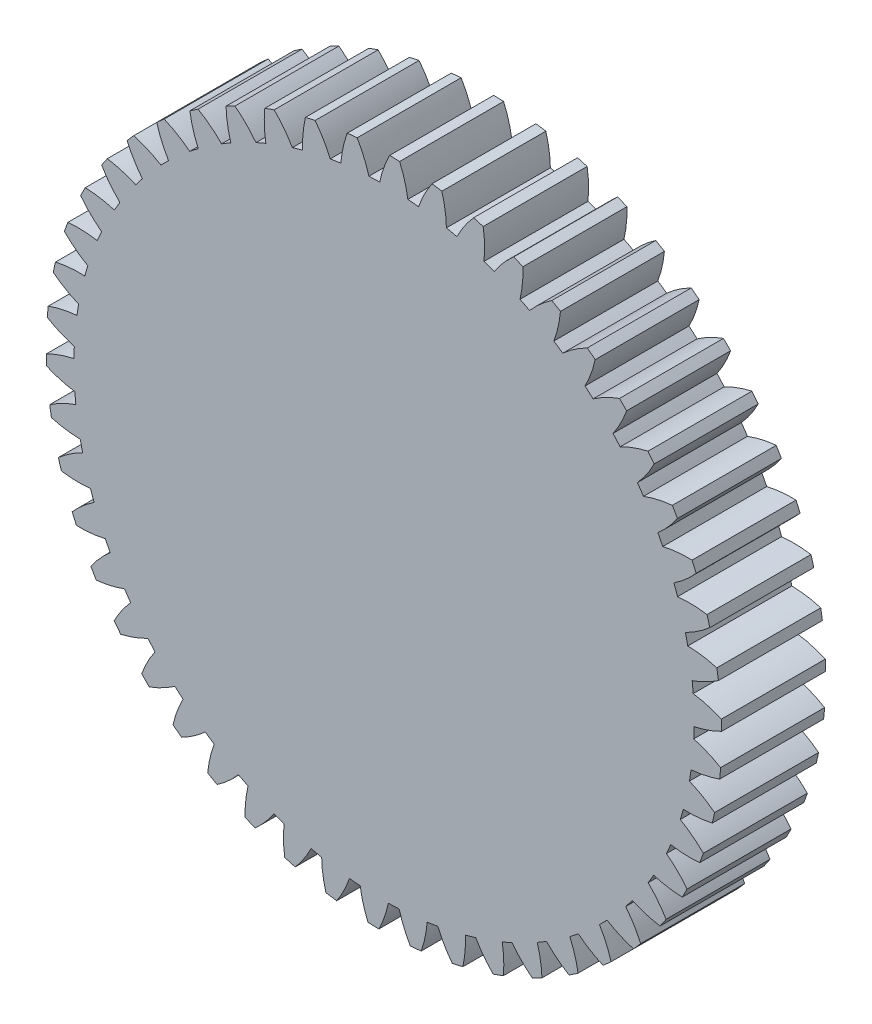
SolidWorks part; units mm, degrees
ref_plane "Front Plane" through (0, 0, 0) normal (0, 0, 1) x (1, 0, 0)
ref_plane "Top Plane" through (0, 0, 0) normal (0, 1, 0) x (1, 0, 0)
ref_plane "Right Plane" through (0, 0, 0) normal (1, 0, 0) x (0, 0, -1)
sketch "Sketch1" plane through (0, 0, 0) normal (0, 0, 1) x (1, 0, 0)
  circle A0 centre (0, 0) radius 104
  dimension "D1" = 208
extrude "Boss-Extrude1" add sketch "Sketch1" along normal blind 32.0177
sketch "Sketch2" plane through (0, 0, 32.0177) normal (0, 0, 1) x (1, 0, 0)
  line L0 (0, 104) -> (0, 0) construction
  line L1 (0, 0) -> (32.1394, 88.3022) construction
  line L2 (32.1394, 88.3022) -> (0, 100) construction
  line L3 (-3.1412, 99.9507) -> (0, 0) construction
  circle A1 centre (0, 0) radius 104
  arc A2 (1.745, 103.9854) -> (-8.2712, 103.6706) centre (0, 0) ccw
  circle A3 centre (0, 0) radius 100 construction
  circle A4 centre (0, 0) radius 93.9693 construction
  arc A5 (-1.3344, 95.3227) -> (-4.6539, 95.2183) centre (0, 0) ccw
  arc A6 (1.745, 103.9854) -> (-1.3344, 95.3227) centre (32.1394, 88.3022) ccw
  arc A7 (-8.2712, 103.6706) -> (-4.6539, 95.2183) centre (-37.6207, 86.1098) cw
  dimension "D3" = 200
  dimension "D4" = 190.664
  dimension "D5" = 187.9385
  dimension "D6" = 20
  dimension "D7" = 3.1416
  dimension "D1" = 0
extrude "Cut-Extrude1" cut sketch "Sketch2" against normal through all
pattern_circular "CirPattern1" count 50 over 360 about axis through (0.005, -0.16, 0) along (0, 0, 1) of "Cut-Extrude1"
sketch "Sketch3" plane through (0, 0, 32.0177) normal (0, 0, 1) x (1, 0, 0)
  line L0 (0, 0) -> (335.0525, 5.0373) construction
  point P3 (174.1006, 6.618)
  point P4 (212.24, 23.1932)
  point P5 (254.1392, 53.8265)
  dimension "Modulo" = 4
  dimension "angulo de presion" = 20
  dimension "numero de dientes" = 50
equation "\"D1@Sketch1\"=\"Modulo@Sketch3\"*(\"numero de dientes@Sketch3\"+2)"
equation "\"D1@Boss-Extrude1\"=(2.15*pi*\"Modulo@Sketch3\")+5"
equation "\"D3@Sketch2\"=\"Modulo@Sketch3\"*\"numero de dientes@Sketch3\""
equation "\"D4@Sketch2\"=\"D1@Sketch1\"-(2*2.167*\"Modulo@Sketch3\")"
equation "\"D5@Sketch2\"=cos(\"angulo de presion@Sketch3\")*\"D3@Sketch2\""
equation "\"D1@CirPattern1\"=\"numero de dientes@Sketch3\""
